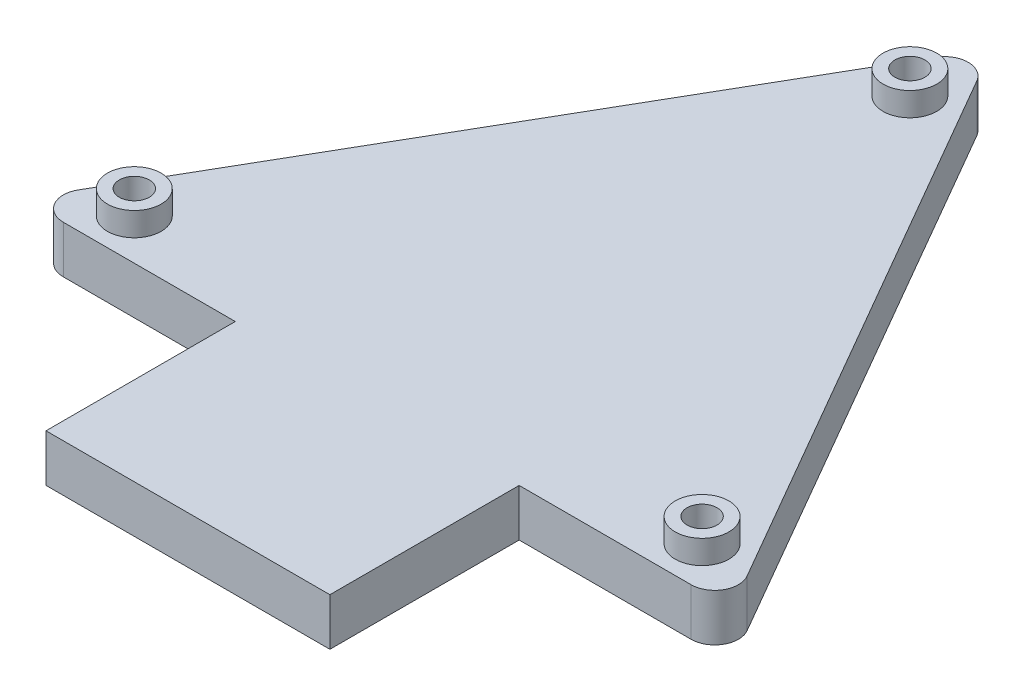
SolidWorks part; units mm, degrees
ref_plane "Front Plane" through (0, 0, 0) normal (0, 0, 1) x (1, 0, 0)
ref_plane "Top Plane" through (0, 0, 0) normal (0, 1, 0) x (1, 0, 0)
ref_plane "Right Plane" through (0, 0, 0) normal (1, 0, 0) x (0, 0, -1)
sketch "Sketch1" plane through (0, 0, 0) normal (0, 1, 0) x (1, 0, 0)
  line L1 (4.3301, 7.5) -> (70.6699, 122.4038)
  line L2 (145.6699, 7.5) -> (79.3301, 122.4038)
  line L3 (-112.5, -64.9519) -> (112.5, 64.9519) construction
  line L4 (75, 259.8076) -> (75, 0) construction
  line L5 (262.5, -64.9519) -> (37.5, 64.9519) construction
  line L7 (45, -40) -> (105, -40)
  line L8 (45, -40) -> (45, 0)
  line L10 (105, -40) -> (105, 0)
  line L12 (45, 0) -> (105, -40) construction
  line L13 (105, 0) -> (141.3397, 0)
  line L14 (8.6603, 0) -> (45, 0)
  circle A0 centre (75, 112.5833) radius 3.175
  circle A2 centre (15, 8.6603) radius 3.175
  circle A3 centre (135, 8.6603) radius 3.175
  arc A4 (141.3397, 0) -> (145.6699, 7.5) centre (141.3397, 5) ccw
  arc A5 (8.6603, 0) -> (4.3301, 7.5) centre (8.6603, 5) cw
  arc A6 (70.6699, 122.4038) -> (79.3301, 122.4038) centre (75, 119.9038) cw
  point P7 (0, 0)
  point P10 (75, 129.9038)
  point P13 (150, 0)
  point P17 (63.3975, -12.265)
  point P21 (63.3975, -12.265)
  point P27 (150, 0)
  point P30 (0, 0)
  point P33 (75, 129.9038)
  point P41 (45, 0)
  dimension "D9" = 5
  dimension "D1" = 120
  dimension "D2" = 150
  dimension "D3" = 150
  dimension "D4" = 150
  dimension "D5" = 120
  dimension "D6" = 120
  dimension "D8" = 60
  dimension "D7" = 40
  dimension "D10" = 36.3397
  dimension "D11" = 36.3397
extrude "Boss-Extrude5" add sketch "Sketch1" along normal blind 10
sketch "Sketch7" plane through (0, 10, 0) normal (0, 1, 0) x (1, 0, 0)
  circle A0 centre (15, 8.6603) radius 3.175 construction
  circle A1 centre (15, 8.6603) radius 3.175
  circle A2 centre (15, 8.6603) radius 5.675
  circle A3 centre (135, 8.6603) radius 5.675
  circle A4 centre (75, 112.5833) radius 3.175
  circle A5 centre (75, 112.5833) radius 3.175
  circle A6 centre (135, 8.6603) radius 3.175
  circle A7 centre (135, 8.6603) radius 3.175
  circle A8 centre (75, 112.5833) radius 5.675
  dimension "D1" = 2.5
  dimension "D4" = 2.5
  dimension "D5" = 2.5
  dimension "D2" = 0
  dimension "D3" = 0
extrude "Boss-Extrude7" add sketch "Sketch7" along normal blind 5
equation "\"D11@Sketch1\"=\"D10@Sketch1\""
